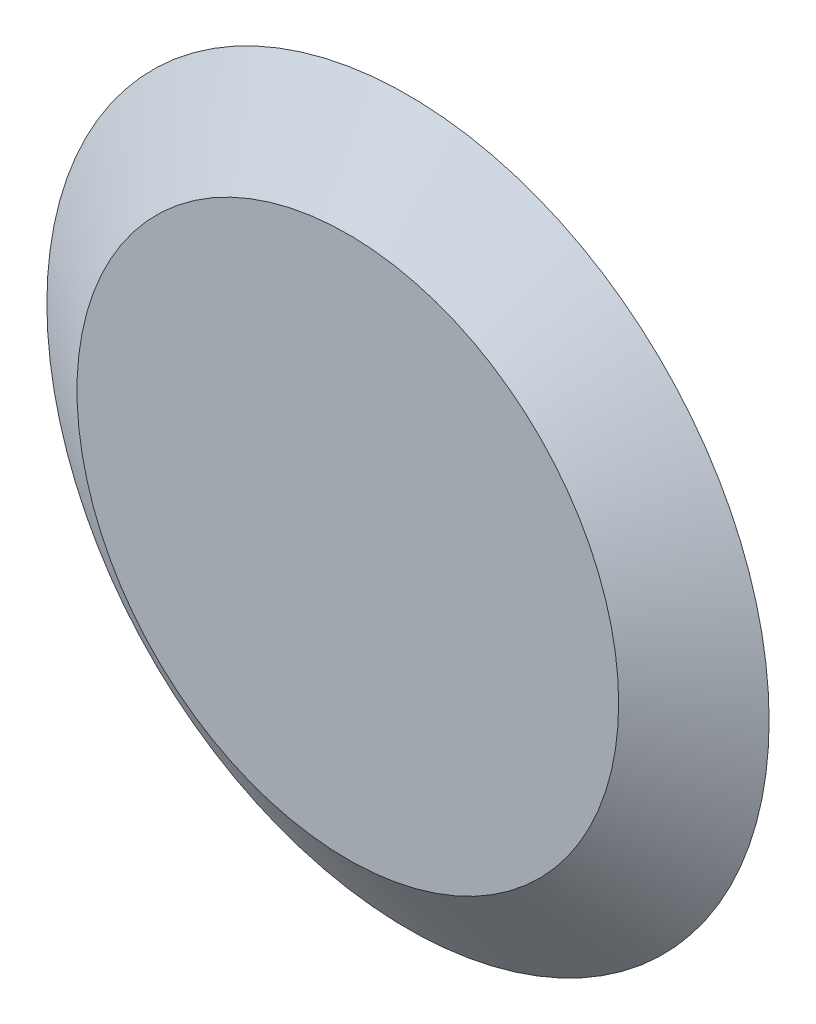
SolidWorks part; units mm, degrees
ref_plane "Plano frontal" through (0, 0, 0) normal (0, 0, 1) x (1, 0, 0)
ref_plane "Plano superior" through (0, 0, 0) normal (0, 1, 0) x (1, 0, 0)
ref_plane "Plano direito" through (0, 0, 0) normal (1, 0, 0) x (0, 0, -1)
sketch "Esboço2" plane through (0, 0, 0) normal (0, 0, 1) x (1, 0, 0)
  circle A0 centre (0, 0) radius 18
ref_plane "Plano1" through (0, 0, 4) normal (0, 0, 1) x (1, 0, 0)
sketch "Esboço3" plane through (0, 0, 4) normal (0, 0, 1) x (1, 0, 0)
  circle A0 centre (0, 0) radius 24
loft "Loft2" add profiles "Esboço3", "Esboço2"
mirror "Espelhar1" about plane through (0, 0, 4) normal (0, 0, 1) of "Loft2"
